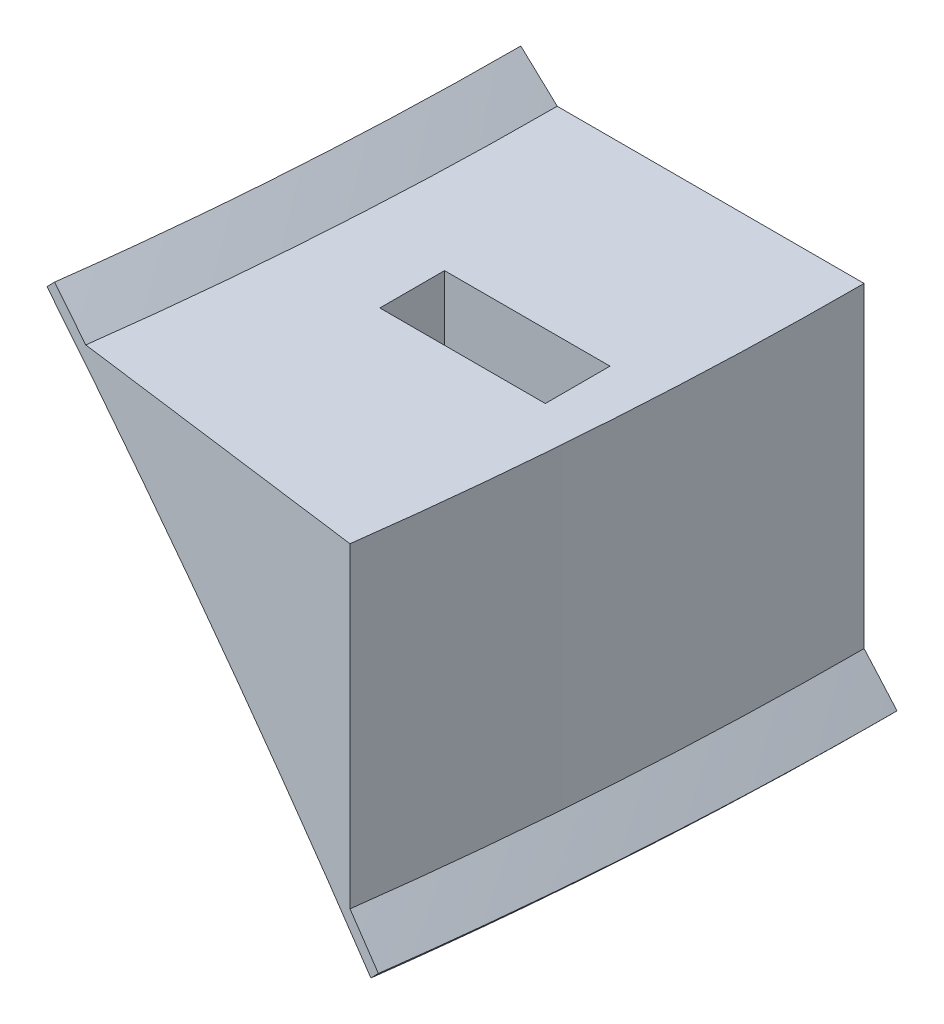
SolidWorks part; units mm, degrees
ref_plane "Front Plane" through (0, 0, 0) normal (0, 0, 1) x (1, 0, 0)
ref_plane "Top Plane" through (0, 0, 0) normal (0, 1, 0) x (1, 0, 0)
ref_plane "Right Plane" through (0, 0, 0) normal (1, 0, 0) x (0, 0, -1)
sketch "Sketch2" plane through (0, 0, 0) normal (0, 0, 1) x (1, 0, 0)
  line L0 (0, 993.0752) -> (0, 990.6)
  line L1 (0, -990.6) -> (0, -993.0752)
  line L4 (742.757, 659.1741) -> (742.757, 722.7151)
  line L5 (742.757, 722.7151) -> (681.0884, 722.7151)
  line L7 (742.9731, -658.9305) -> (742.9731, -735.9651)
  line L8 (742.9731, -735.9651) -> (666.7487, -735.9651)
  arc A0 (0, 990.6) -> (0, -990.6) centre (0, 0) cw
  arc A1 (0, -993.0752) -> (666.7487, -735.9651) centre (0, 0) ccw
  arc A2 (681.0884, 722.7151) -> (0, 993.0752) centre (0, 0) ccw
  arc A3 (742.9731, -658.9305) -> (742.757, 659.1741) centre (0, 0) ccw
  dimension "D1" = 990.6
revolve "Revolve2" add sketch "Sketch2" angle 7.5 about L0
sketch "Sketch4" plane through (0, -735.9651, 0) normal (0, -1, 0) x (1, 0, 0)
  line L1 (688.6335, 42.5614) -> (721.8835, 42.5614)
  line L2 (688.6335, 42.5614) -> (688.6335, 55.5614)
  line L3 (688.6335, 55.5614) -> (721.8835, 55.5614)
  line L4 (721.8835, 42.5614) -> (721.8835, 55.5614)
sketch "Sketch7" plane through (0, 722.7151, 0) normal (0, 1, 0) x (-1, 0, 0)
  line L1 (-731.6247, 39.9227) -> (-698.3747, 39.9227)
  line L2 (-731.6247, 39.9227) -> (-731.6247, 52.9227)
  line L3 (-731.6247, 52.9227) -> (-698.3747, 52.9227)
  line L4 (-698.3747, 39.9227) -> (-698.3747, 52.9227)
extrude "Cut-Extrude5" cut sketch "Sketch4" against normal blind 19
extrude "Cut-Extrude7" cut sketch "Sketch7" against normal blind 19
sketch "Sketch8" plane through (0, 0, 0) normal (0, 0, 1) x (1, 0, 0)
  line L0 (0, 0) -> (764.184, 622.2454) construction
  ellipse E0 centre (0, 0) end of major axis (0, -990.6) minor radius 982.1253 (0, -990.6) -> (0, 990.6) ccw construction
ref_plane "Plane1" through (770.0754, 627.0425, 0) normal (0.7754, 0.6314, 0) x (0, 0, -1)
sketch "Sketch9" plane through (770.0754, 627.0425, 0) normal (0.7754, 0.6314, 0) x (0, 0, -1)
  line L1 (-118.3397, 200.2044) -> (70.2962, 200.2044)
  line L2 (-118.3397, 200.2044) -> (-118.3397, 832.2458)
  line L3 (-118.3397, 832.2458) -> (70.2962, 832.2458)
  line L4 (70.2962, 200.2044) -> (70.2962, 832.2458)
extrude "Cut-Extrude8" cut sketch "Sketch9" against normal through all both and the other way through all
sketch "Sketch10" plane through (770.0754, 627.0425, 0) normal (0.7754, 0.6314, 0) x (0, 0, -1)
  line L1 (-213.6342, 19.3196) -> (223.2937, 19.3196)
  line L2 (-213.6342, 19.3196) -> (-213.6342, -1582.1557)
  line L3 (-213.6342, -1582.1557) -> (223.2937, -1582.1557)
  line L4 (223.2937, 19.3196) -> (223.2937, -1582.1557)
extrude "Cut-Extrude9" cut sketch "Sketch10" against normal through all both and the other way through all
sketch "Sketch11" plane through (0, 0, 0) normal (0, 0, 1) x (1, 0, 0)
  line L0 (698.8874, 702.029) -> (0, 0) construction
  arc A0 (755.8112, 640.3419) -> (625.8923, 767.8198) centre (0, 0) ccw construction
ref_plane "Plane2" through (700.6337, 703.7832, 0) normal (0.7055, 0.7087, 0) x (0.7087, -0.7055, 0)
sketch "Sketch12" plane through (700.6337, 703.7832, 0) normal (0.7055, 0.7087, 0) x (0.7087, -0.7055, 0)
  line L0 (66.7785, -97.8782) -> (65.1803, -115.0076)
  line L1 (65.1803, -115.0076) -> (86.9998, -115.0076)
  line L2 (86.9998, -115.0076) -> (98.4507, 7.7236)
  line L3 (98.4507, 7.7236) -> (71.325, 10.2544)
  line L4 (71.325, 10.2544) -> (71.325, 0)
  line L5 (-41.2946, -87.9709) -> (-47.2104, -112.2853)
  line L6 (-47.2104, -112.2853) -> (-119.1199, -100.1281)
  line L7 (-119.1199, -100.1281) -> (-110.5768, 17.6625)
  line L8 (-110.5768, 17.6625) -> (-37.2084, 15.1488)
  line L9 (-37.2084, 15.1488) -> (-37.2084, 0)
  spline S0 degree 3 poles (-2038.997, 939.2258) (-732.8618, -1421.3391) (36.7565, -768.7561) (103.6661, 671.7076) (-601.166, 1459.763) (-2111.264, -656.0793) knots -21.543932 -21.543932 -21.543932 -21.543932 0.5 0.5 22.575687 22.575687 22.575687 22.575687 only from (66.7785, -97.8782) to (71.325, 0)
  spline S1 degree 3 poles (66.7785, -97.8782) (68.2919, -81.6571) (69.4289, -65.3672) (70.9455, -32.7181) (71.325, -16.3591) (71.325, 0) knots 0 0 0 0 0.5 0.5 1 1 1 1
  spline S2 degree 3 poles (-2092.711, 1278.814) (-830.289, -1333.6026) (-69.771, -723.0888) (-6.6452, 635.9161) (-706.1653, 1384.5869) (-2212.9064, -980.2823) knots -22.638851 -22.638851 -22.638851 -22.638851 0.5 0.5 23.672587 23.672587 23.672587 23.672587 only from (-41.2946, -87.9709) to (-37.2084, 0)
  spline S3 degree 3 poles (-41.2946, -87.9709) (-39.9346, -73.3942) (-38.9126, -58.7538) (-37.5496, -29.4089) (-37.2084, -14.7044) (-37.2084, 0) knots 0 0 0 0 0.5 0.5 1 1 1 1
  dimension "D1" = 10
  dimension "D2" = 10
extrude "Cut-Extrude10" cut sketch "Sketch12" against normal through all both and the other way through all contours L5 S3 L9 L8 L7 L6 | S1 L0 L1 L2 L3 L4
